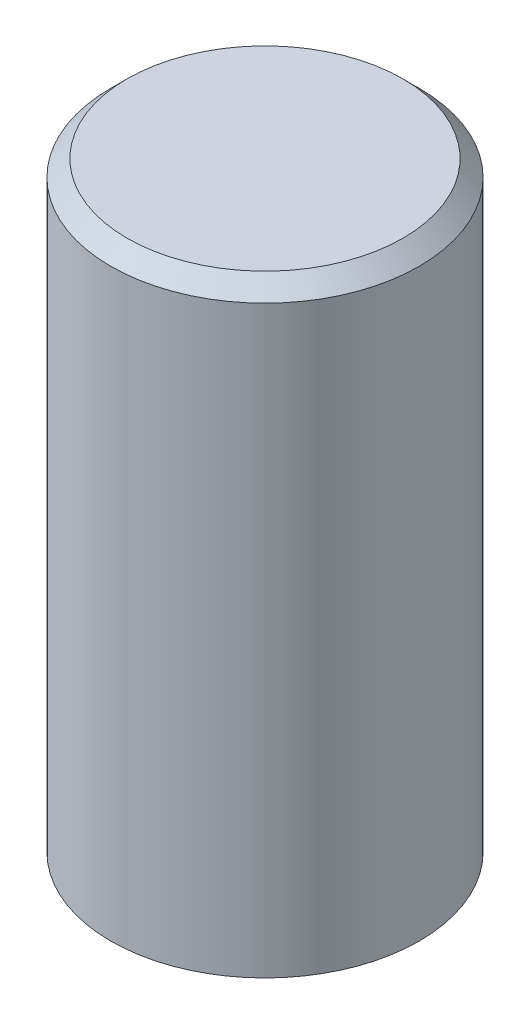
SolidWorks part; units mm, degrees
ref_plane "前视基准面" through (0, 0, 0) normal (0, 0, 1) x (1, 0, 0)
ref_plane "上视基准面" through (0, 0, 0) normal (0, 1, 0) x (1, 0, 0)
ref_plane "右视基准面" through (0, 0, 0) normal (1, 0, 0) x (0, 0, -1)
other "Configuration Table"
sketch "草图1" plane through (0, 0, 0) normal (0, 1, 0) x (1, 0, 0)
  circle A0 centre (0, 0) radius 9.5
  dimension "D1" = 19
extrude "凸台-拉伸1" add sketch "草图1" along normal blind 37
sketch "草图2" plane through (0, 0, 0) normal (0, -1, 0) x (1, 0, 0)
  circle A0 centre (0, 0) radius 7.5
  dimension "D1" = 15
extrude "切除-拉伸1" cut sketch "草图2" against normal blind 7
chamfer "倒角1" distance 1 angle 45 1 edges at (0, 37, 9.5)
chamfer "倒角2" distance 0.5 angle 45 1 edges at (0, 0, -7.5)
